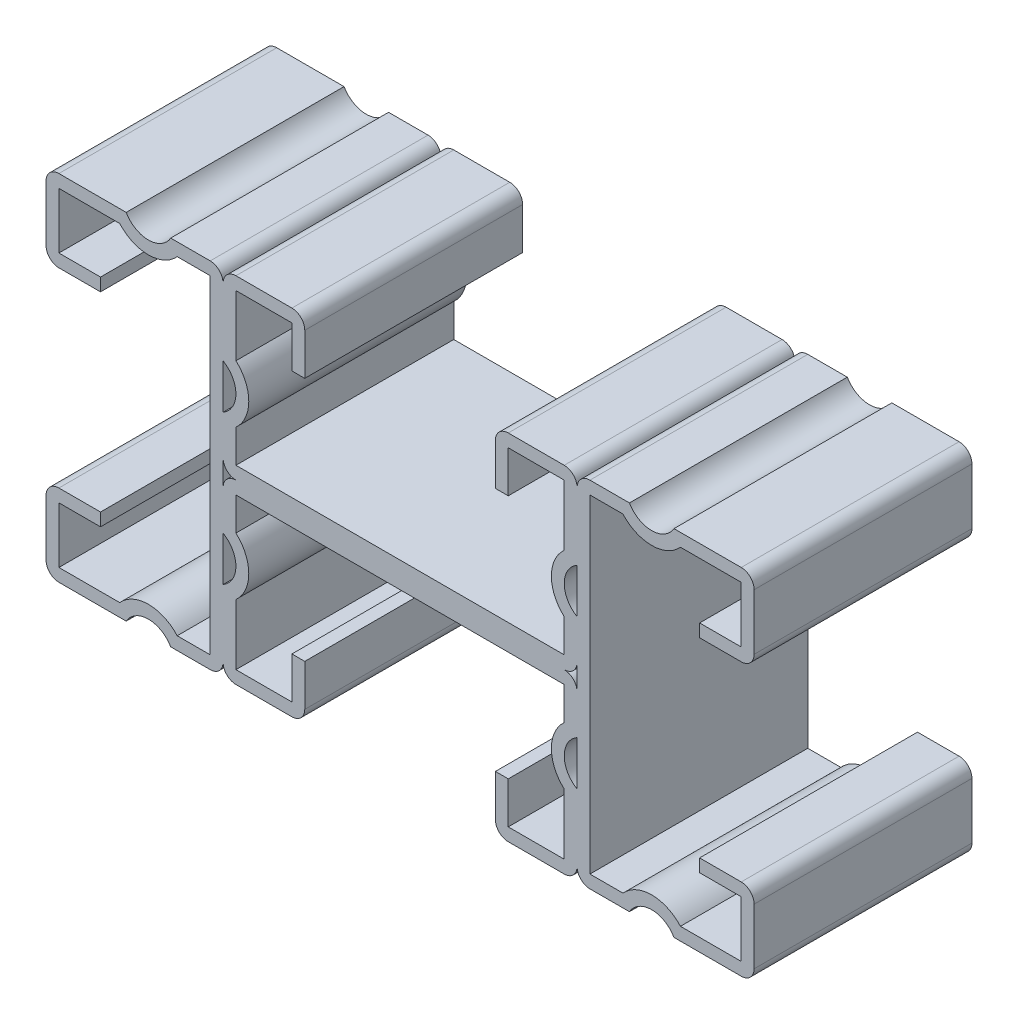
SolidWorks part; units mm, degrees
ref_plane "Plane1" through (0, 0, 0) normal (0, 0, 1) x (1, 0, 0)
ref_plane "Plane2" through (0, 0, 0) normal (0, 1, 0) x (1, 0, 0)
ref_plane "Plane3" through (0, 0, 0) normal (1, 0, 0) x (0, 0, -1)
sketch "Sketch1" plane through (0, 0, 0) normal (0, 0, 1) x (1, 0, 0)
  line L0 (-20.6375, 19.1389) -> (-20.6375, 11.2952)
  line L1 (-20.6375, 6.1038) -> (-20.6375, 1.4986)
  line L2 (-19.1389, 0) -> (19.1389, 0)
  line L3 (20.6375, 1.4986) -> (20.6375, 6.1038)
  line L4 (20.6375, 11.2952) -> (20.6375, 19.1389)
  line L5 (19.1389, 20.6375) -> (12.6111, 20.6375)
  line L6 (11.1125, 19.1389) -> (11.1125, 14.2875)
  line L7 (-19.1389, 20.6375) -> (-12.6111, 20.6375)
  line L8 (-11.1125, 19.1389) -> (-11.1125, 14.2875)
  line L9 (19.1389, 3.4236) -> (19.1389, 6.4516) construction
  line L10 (-19.1389, 15.1511) -> (-19.1389, 3.4236) construction
  line L11 (-12.6111, 19.1389) -> (-12.6111, 14.2875)
  line L12 (-19.1389, 19.1389) -> (-12.6111, 19.1389)
  line L13 (-19.1389, 19.1389) -> (-19.1389, 12.0505)
  line L14 (-19.1389, 5.3485) -> (-19.1389, 1.4986)
  line L15 (-19.1389, 1.4986) -> (19.1389, 1.4986)
  line L16 (19.1389, 1.4986) -> (19.1389, 5.3485)
  line L17 (19.1389, 12.0505) -> (19.1389, 19.1389)
  line L18 (19.1389, 19.1389) -> (12.6111, 19.1389)
  line L19 (12.6111, 19.1389) -> (12.6111, 14.2875)
  line L20 (-12.6111, 14.2875) -> (-11.1125, 14.2875)
  line L21 (11.1125, 14.2875) -> (12.6111, 14.2875)
  arc A0 (20.6375, 11.2952) -> (20.6375, 6.1038) centre (22.1361, 8.6995) ccw
  arc A1 (-20.6375, 6.1038) -> (-20.6375, 11.2952) centre (-22.1361, 8.6995) ccw
  arc A2 (-12.6111, 20.6375) -> (-11.1125, 19.1389) centre (-12.6111, 19.1389) cw
  arc A3 (-20.6375, 19.1389) -> (-19.1389, 20.6375) centre (-19.1389, 19.1389) cw
  arc A4 (-19.1389, 0) -> (-20.6375, 1.4986) centre (-19.1389, 1.4986) cw
  arc A5 (20.6375, 1.4986) -> (19.1389, 0) centre (19.1389, 1.4986) cw
  arc A6 (19.1389, 20.6375) -> (20.6375, 19.1389) centre (19.1389, 19.1389) cw
  arc A7 (11.1125, 19.1389) -> (12.6111, 20.6375) centre (12.6111, 19.1389) cw
  arc A8 (-19.1389, 5.3485) -> (-19.1389, 12.0505) centre (-22.1361, 8.6995) ccw
  arc A9 (19.1389, 12.0505) -> (19.1389, 5.3485) centre (22.1361, 8.6995) ccw
  dimension "D9" = 2.9972
  dimension "D10" = 2.9972
  dimension "Width" = 41.275
  dimension "D6" = 22.225
  dimension "edge" = 9.525
  dimension "Lip" = 6.35
  dimension "D1" = 20.6375
  dimension "D2" = 8.6995
  dimension "gauge" = 1.4986
extrude "Base-Extrude" add sketch "Sketch1" along normal mid plane 25.4
mirror "Mirror1" about plane through (0, 0, 0) normal (0, 1, 0) of "Base-Extrude"
sketch "Sketch2" plane through (20.1612, 0.1588, 0) normal (0, 0, 1) x (0, -1, 0)
  line L0 (-20.4788, 19.6152) -> (-20.4788, 11.7714)
  line L1 (-20.4788, 6.5801) -> (-20.4788, 1.9749)
  line L2 (-18.9802, 0.4763) -> (19.2976, 0.4763)
  line L3 (20.7962, 1.9749) -> (20.7962, 6.5801)
  line L4 (20.7962, 11.7714) -> (20.7962, 19.6152)
  line L5 (19.2977, 21.1138) -> (12.7698, 21.1138)
  line L6 (11.2712, 19.6152) -> (11.2712, 14.7638)
  line L7 (-18.9802, 21.1138) -> (-12.4523, 21.1138)
  line L8 (-10.9538, 19.6152) -> (-10.9538, 14.7638)
  line L9 (19.2976, 3.8998) -> (19.2976, 6.9279) construction
  line L10 (-18.9802, 15.6274) -> (-18.9802, 3.8998) construction
  line L11 (-12.4523, 19.6152) -> (-12.4524, 14.7638)
  line L12 (-18.9802, 19.6152) -> (-12.4523, 19.6152)
  line L13 (-18.9802, 19.6152) -> (-18.9802, 12.5267)
  line L14 (-18.9802, 5.8248) -> (-18.9802, 1.9749)
  line L15 (-18.9802, 1.9749) -> (19.2976, 1.9749)
  line L16 (19.2976, 1.9749) -> (19.2976, 5.8248)
  line L17 (19.2977, 12.5267) -> (19.2977, 19.6152)
  line L18 (19.2977, 19.6152) -> (12.7698, 19.6152)
  line L19 (12.7698, 19.6152) -> (12.7698, 14.7638)
  line L20 (-12.4524, 14.7638) -> (-10.9538, 14.7638)
  line L21 (11.2712, 14.7638) -> (12.7698, 14.7638)
  arc A0 (20.7962, 11.7714) -> (20.7962, 6.5801) centre (22.2948, 9.1758) ccw
  arc A1 (-20.4788, 6.5801) -> (-20.4788, 11.7714) centre (-21.9774, 9.1758) ccw
  arc A2 (-12.4523, 21.1138) -> (-10.9538, 19.6152) centre (-12.4523, 19.6152) cw
  arc A3 (-20.4788, 19.6152) -> (-18.9802, 21.1138) centre (-18.9802, 19.6152) cw
  arc A4 (-18.9802, 0.4763) -> (-20.4788, 1.9749) centre (-18.9802, 1.9749) cw
  arc A5 (20.7962, 1.9749) -> (19.2976, 0.4763) centre (19.2976, 1.9749) cw
  arc A6 (19.2977, 21.1138) -> (20.7962, 19.6152) centre (19.2977, 19.6152) cw
  arc A7 (11.2712, 19.6152) -> (12.7698, 21.1138) centre (12.7698, 19.6152) cw
  arc A8 (-18.9802, 5.8248) -> (-18.9802, 12.5267) centre (-21.9774, 9.1758) ccw
  arc A9 (19.2977, 12.5267) -> (19.2976, 5.8248) centre (22.2948, 9.1758) ccw
  dimension "D1" = 20.6375
  dimension "D9" = 2.9972
  dimension "D10" = 2.9972
  dimension "D2" = 8.6995
  dimension "D3" = 20.6375
  dimension "Width" = 41.275
  dimension "D6" = 22.225
  dimension "edge" = 9.525
  dimension "Lip" = 6.35
  dimension "D4" = 20.6375
  dimension "gauge" = 1.4986
extrude "Boss-Extrude1" add sketch "Sketch2" along normal mid plane 25.4
mirror "Mirror2" about plane through (0, 0, 0) normal (1, 0, 0) of "Boss-Extrude1"
equation "\"D1@Sketch1\" = \"Width@Sketch1\" / 2"
equation "\"D6@Sketch1\" = \"Width@Sketch1\" - 2 * \"edge@Sketch1\""
equation "\"D10@Sketch1\" = 2 * \"gauge@Sketch1\""
equation "\"D9@Sketch1\" = \"D10@Sketch1\""
equation "\"D1@Boss-Extrude1\" = \"D1@Base-Extrude\""
